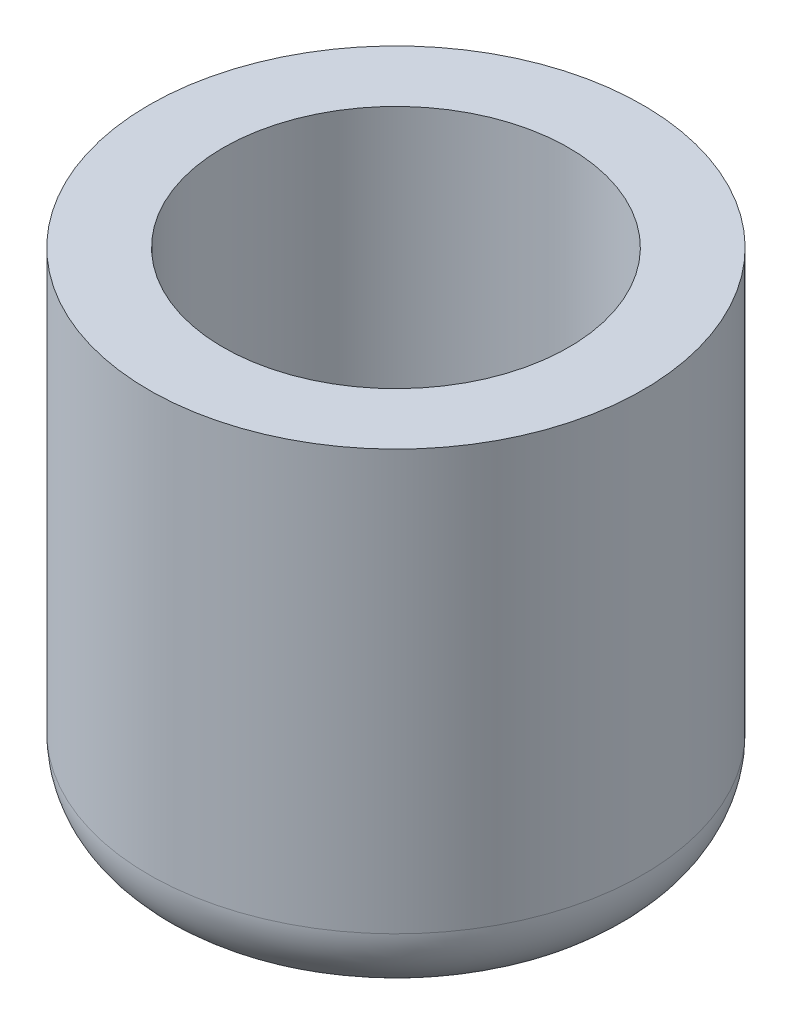
SolidWorks part; units mm, degrees
ref_plane "Спереди" through (0, 0, 0) normal (0, 0, 1) x (1, 0, 0)
ref_plane "Сверху" through (0, 0, 0) normal (0, 1, 0) x (1, 0, 0)
ref_plane "Справа" through (0, 0, 0) normal (1, 0, 0) x (0, 0, -1)
sketch "Эскиз1" plane through (0, 0, 0) normal (0, 0, 1) x (1, 0, 0)
  line L0 (-5, -10) -> (-5, 0)
  line L1 (-5, -10) -> (0, -10)
  line L2 (0, 0) -> (0, -10) construction
  line L3 (0, 0) -> (-5, 0) construction
  dimension "D1" = 10
  dimension "D2" = 10
revolve "Повернуть-Тонкостенный1" add sketch "Эскиз1" angle 360 about L2
fillet "Скругление1" radius 1.5 1 edges at (-5, -10, 0)
sketch "Эскиз2" plane through (0, 0, 0) normal (0, 1, 0) x (1, 0, 0)
  circle A2 centre (0, 0) radius 15
  circle A3 centre (0, 0) radius 15
  dimension "D1" = 10
extrude "Вырез-Вытянуть1" [suppressed] cut sketch "Эскиз2" against normal up to vertex
